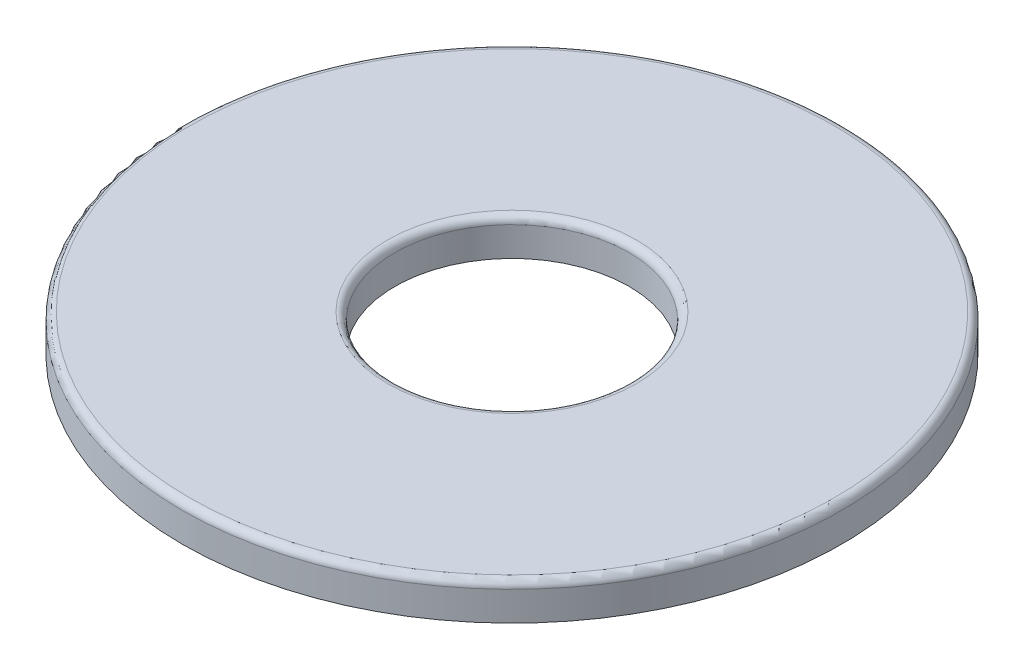
SolidWorks part; units mm, degrees
material "AISI Typ 316L stal nierdzewna"
ref_plane "Płaszczyzna przednia" through (0, 0, 0) normal (0, 0, 1) x (1, 0, 0)
ref_plane "Płaszczyzna górna" through (0, 0, 0) normal (0, 1, 0) x (1, 0, 0)
ref_plane "Płaszczyzna prawa" through (0, 0, 0) normal (1, 0, 0) x (0, 0, -1)
sketch "Szkic1" plane through (0, 0, 0) normal (0, 1, 0) x (1, 0, 0)
  circle A0 centre (0, 0) radius 4.5
  circle A1 centre (0, 0) radius 1.6
  dimension "D1" = 9
  dimension "D2" = 3.2
extrude "Dodanie-wyciągnięcie1" add sketch "Szkic1" along normal blind 0.5
fillet "Zaokrąglenie1" radius 0.1 2 edges at (0, 0.5, 1.6) (0, 0.5, 4.5)
